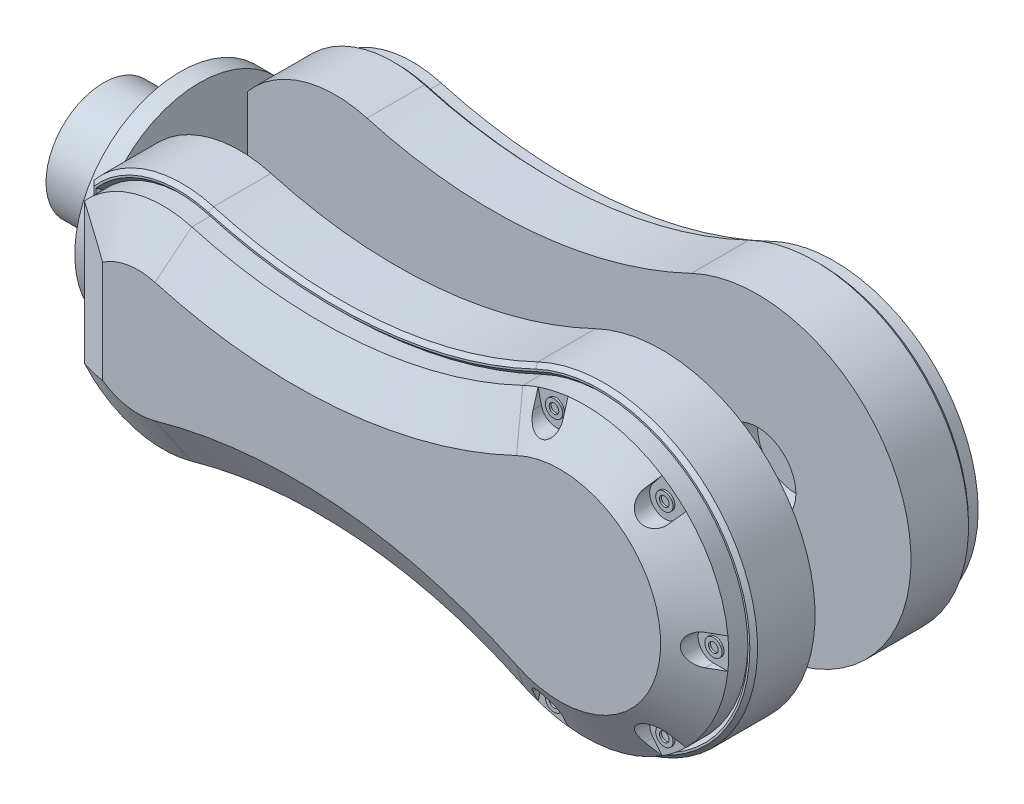
SolidWorks part; units mm, degrees
ref_plane "Front Plane" through (0, 0, 0) normal (0, 0, 1) x (1, 0, 0)
ref_plane "Top Plane" through (0, 0, 0) normal (0, 1, 0) x (1, 0, 0)
ref_plane "Right Plane" through (0, 0, 0) normal (1, 0, 0) x (0, 0, -1)
sketch "Sketch1" plane through (0, 0, 0) normal (1, 0, 0) x (0, 0, -1)
  circle A0 centre (0, 0) radius 27.5
  dimension "D1" = 55
extrude "Boss-Extrude1" add sketch "Sketch1" along normal blind 5
ref_plane "Plane1" through (0, 0, 27.5) normal (0, 0, 1) x (1, 0, 0)
sketch "Sketch2" plane through (0, 0, 27.5) normal (0, 0, 1) x (1, 0, 0)
  line L0 (5, 0) -> (138, 0) construction
  line L1 (5, -27.5) -> (5, 27.5) construction
  line L4 (5, -19.2614) -> (5, 19.2614)
  arc A0 (5, -19.2614) -> (36.1818, -28.8627) centre (28, 0) ccw
  arc A1 (120.7273, -36.0784) -> (120.7273, 36.0784) centre (138, 0) ccw
  arc A2 (36.1818, 28.8627) -> (120.7273, 36.0784) centre (68.9091, 144.3137) ccw
  arc A3 (36.1818, -28.8627) -> (120.7273, -36.0784) centre (68.9091, -144.3137) cw
  arc A4 (36.1818, 28.8627) -> (5, 19.2614) centre (28, 0) ccw
  dimension "D1" = 80
  dimension "D4" = 60
  dimension "D5" = 120
  dimension "D2" = 110
  dimension "D3" = 23
extrude "Boss-Extrude2" add sketch "Sketch2" against normal blind 15
sketch "Sketch3" plane through (0, 0, 27.5) normal (0, 0, 1) x (1, 0, 0)
  line L0 (7.5, 18.3303) -> (7.5, 0)
  line L1 (7.5, 0) -> (7.5, -18.3303)
  line L2 (5, 19.2614) -> (5, 0)
  line L3 (5, 0) -> (5, -19.2614)
  line L4 (5, 19.2614) -> (5, 0)
  line L5 (5, 0) -> (5, -19.2614)
  arc A0 (35.5, 26.4575) -> (7.5, 18.3303) centre (28, 0) ccw
  arc A1 (7.5, -18.3303) -> (35.5, -26.4575) centre (28, 0) ccw
  arc A2 (121.8068, -33.8235) -> (35.5, -26.4575) centre (68.9091, -144.3137) ccw
  arc A3 (121.8068, -33.8235) -> (121.8068, 33.8235) centre (138, 0) ccw
  arc A4 (35.5, 26.4575) -> (121.8068, 33.8235) centre (68.9091, 144.3137) ccw
  arc A5 (36.1818, 28.8627) -> (5, 19.2614) centre (28, 0) ccw
  arc A6 (5, -19.2614) -> (36.1818, -28.8627) centre (28, 0) ccw
  arc A7 (120.7273, -36.0784) -> (36.1818, -28.8627) centre (68.9091, -144.3137) ccw
  arc A8 (120.7273, -36.0784) -> (120.7273, 36.0784) centre (138, 0) ccw
  arc A9 (36.1818, 28.8627) -> (120.7273, 36.0784) centre (68.9091, 144.3137) ccw
  arc A11 (5, -19.2614) -> (36.1818, -28.8627) centre (28, 0) ccw
  arc A12 (120.7273, -36.0784) -> (36.1818, -28.8627) centre (68.9091, -144.3137) ccw
  arc A13 (120.7273, -36.0784) -> (120.7273, 36.0784) centre (138, 0) ccw
  arc A20 (36.1818, 28.8627) -> (120.7273, 36.0784) centre (68.9091, 144.3137) ccw construction
  arc A21 (36.1818, 28.8627) -> (5, 19.2614) centre (28, 0) ccw construction
  dimension "D1" = 0
  dimension "D2" = 2.5
extrude "Boss-Extrude3" add sketch "Sketch3" along normal blind 5 contours A4 A3 A2 A1 L1 L0 A0
sketch "Sketch7" plane through (0, 0, 27.5) normal (0, 0, 1) x (1, 0, 0)
  line L0 (7.5, 18.3303) -> (7.5, -18.3303) construction
  line L1 (7.5, 18.3303) -> (7.5, -18.3303)
  line L2 (5, 19.2614) -> (5, 0)
  line L3 (5, 0) -> (5, -19.2614)
  line L4 (5, 19.2614) -> (5, 0)
  line L5 (5, 0) -> (5, -19.2614)
  arc A0 (35.5, 26.4575) -> (121.8068, 33.8235) centre (68.9091, 144.3137) ccw construction
  arc A1 (35.5, 26.4575) -> (121.8068, 33.8235) centre (68.9091, 144.3137) ccw
  arc A2 (35.5, 26.4575) -> (7.5, 18.3303) centre (28, 0) ccw construction
  arc A3 (121.8068, -33.8235) -> (121.8068, 33.8235) centre (138, 0) ccw construction
  arc A4 (121.8068, -33.8235) -> (35.5, -26.4575) centre (68.9091, -144.3137) ccw construction
  arc A5 (36.1818, 28.8627) -> (5, 19.2614) centre (28, 0) ccw
  arc A6 (5, -19.2614) -> (36.1818, -28.8627) centre (28, 0) ccw
  arc A7 (120.7273, -36.0784) -> (36.1818, -28.8627) centre (68.9091, -144.3137) ccw
  arc A8 (120.7273, -36.0784) -> (120.7273, 36.0784) centre (138, 0) ccw
  arc A9 (36.1818, 28.8627) -> (120.7273, 36.0784) centre (68.9091, 144.3137) ccw
  arc A10 (36.1818, 28.8627) -> (5, 19.2614) centre (28, 0) ccw
  arc A11 (5, -19.2614) -> (36.1818, -28.8627) centre (28, 0) ccw
  arc A12 (120.7273, -36.0784) -> (36.1818, -28.8627) centre (68.9091, -144.3137) ccw
  arc A13 (120.7273, -36.0784) -> (120.7273, 36.0784) centre (138, 0) ccw
  arc A14 (36.1818, 28.8627) -> (120.7273, 36.0784) centre (68.9091, 144.3137) ccw
  arc A15 (7.5, -18.3303) -> (35.5, -26.4575) centre (28, 0) ccw construction
  arc A16 (35.5, 26.4575) -> (7.5, 18.3303) centre (28, 0) ccw
  arc A17 (121.8068, -33.8235) -> (121.8068, 33.8235) centre (138, 0) ccw
  arc A18 (121.8068, -33.8235) -> (35.5, -26.4575) centre (68.9091, -144.3137) ccw
  arc A19 (7.5, -18.3303) -> (35.5, -26.4575) centre (28, 0) ccw
  dimension "D1" = 0
extrude "Boss-Extrude4" add sketch "Sketch7" along normal blind 1 draft 45
sketch "Sketch8" plane through (0, 0, 32.5) normal (0, 0, 1) x (1, 0, 0)
  line L1 (7.5, 18.3303) -> (7.5, -18.3303)
  line L2 (7.5, 18.3303) -> (7.5, -18.3303)
  arc A5 (35.5, 26.4575) -> (7.5, 18.3303) centre (28, 0) ccw
  arc A6 (7.5, -18.3303) -> (35.5, -26.4575) centre (28, 0) ccw
  arc A7 (121.8068, -33.8235) -> (35.5, -26.4575) centre (68.9091, -144.3137) ccw
  arc A8 (121.8068, -33.8235) -> (121.8068, 33.8235) centre (138, 0) ccw
  arc A9 (35.5, 26.4575) -> (121.8068, 33.8235) centre (68.9091, 144.3137) ccw
  arc A10 (35.5, 26.4575) -> (7.5, 18.3303) centre (28, 0) ccw
  arc A11 (7.5, -18.3303) -> (35.5, -26.4575) centre (28, 0) ccw
  arc A12 (121.8068, -33.8235) -> (35.5, -26.4575) centre (68.9091, -144.3137) ccw
  arc A13 (121.8068, -33.8235) -> (121.8068, 33.8235) centre (138, 0) ccw
  arc A14 (35.5, 26.4575) -> (121.8068, 33.8235) centre (68.9091, 144.3137) ccw
  dimension "D1" = 0
extrude "Boss-Extrude5" add sketch "Sketch8" along normal blind 6.5 draft 60
sketch "Sketch9" plane through (0, 0, 39) normal (0, 0, 1) x (1, 0, 0)
  line L0 (0, 0) -> (196.2588, 0) construction
  line L1 (171.5, 4) -> (176.2476, 4)
  line L2 (176.2476, 4) -> (176.2476, -4)
  line L3 (171.5, -4) -> (176.2476, -4)
  arc A0 (171.5, 4) -> (171.5, -4) centre (171.5, 0) ccw
  arc A1 (121.8068, -33.8235) -> (121.8068, 33.8235) centre (138, 0) ccw construction
  arc A2 (121.8068, -33.8235) -> (121.8068, 33.8235) centre (138, 0) ccw
  point P9 (176.2476, 0)
  dimension "D1" = 8
extrude "Cut-Extrude1" cut sketch "Sketch9" against normal blind 6.5 contours A0 L0 A2 L1 | L0 A0 L3 A2 | A2 L0 L2 L1 | L0 A2 L3 L2
sketch "Sketch10" plane through (0, 0, 32.5) normal (0, 0, 1) x (1, 0, 0)
  line L0 (167.5, 0) -> (176.5, 0) construction
  arc A0 (171.5, 4) -> (171.5, -4) centre (171.5, 0) ccw construction
  arc A1 (121.375, -34.7255) -> (121.375, 34.7255) centre (138, 0) ccw construction
  circle A2 centre (172, 0) radius 1.25
  circle A3 centre (172, 0) radius 2.25
  dimension "D1" = 2.5
  dimension "D2" = 1
extrude "Boss-Extrude6" add sketch "Sketch10" along normal blind 0.5
pattern_circular "CirPattern1" count 7 over 360 about axis through (138, 0, 0) along (0, 0, 1) skipping 3, 4 of "Cut-Extrude1", "Boss-Extrude6"
mirror "Mirror1" about plane through (0, 0, 0) normal (0, 0, 1) of "CirPattern1", "Boss-Extrude6", "Cut-Extrude1", "Boss-Extrude5", "Boss-Extrude4", "Boss-Extrude3", "Boss-Extrude2"
sketch "Sketch11" plane through (0, 0, 0) normal (-1, 0, 0) x (0, 0, 1)
  circle A0 centre (0, 0) radius 15
  dimension "D1" = 30
extrude "Boss-Extrude7" add sketch "Sketch11" along normal blind 20
sketch "Sketch12" plane through (0, 0, -12.5) normal (0, 0, 1) x (1, 0, 0)
  circle A0 centre (138, 0) radius 10
  dimension "D1" = 20
extrude "Cut-Extrude2" cut sketch "Sketch12" against normal blind 10
ref_point "Point1"
